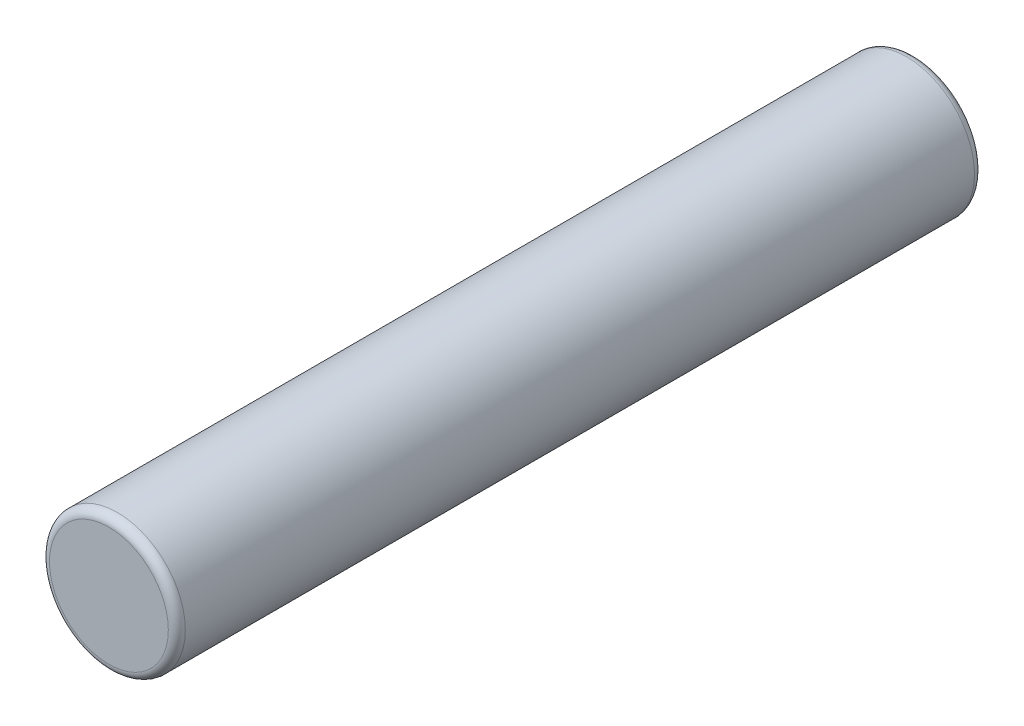
SolidWorks part; units mm, degrees
ref_plane "Front Plane" through (0, 0, 0) normal (0, 0, 1) x (1, 0, 0)
ref_plane "Top Plane" through (0, 0, 0) normal (0, 1, 0) x (1, 0, 0)
ref_plane "Right Plane" through (0, 0, 0) normal (1, 0, 0) x (0, 0, -1)
sketch "Sketch1" plane through (0, 0, 0) normal (0, 0, 1) x (1, 0, 0)
  circle A0 centre (0, 0) radius 20.32
  dimension "D1" = 40.64
extrude "Boss-Extrude1" add sketch "Sketch1" along normal blind 241.3
fillet "Fillet1" radius 2.54 2 edges at (20.32, 0, 0) (20.32, 0, 241.3)
